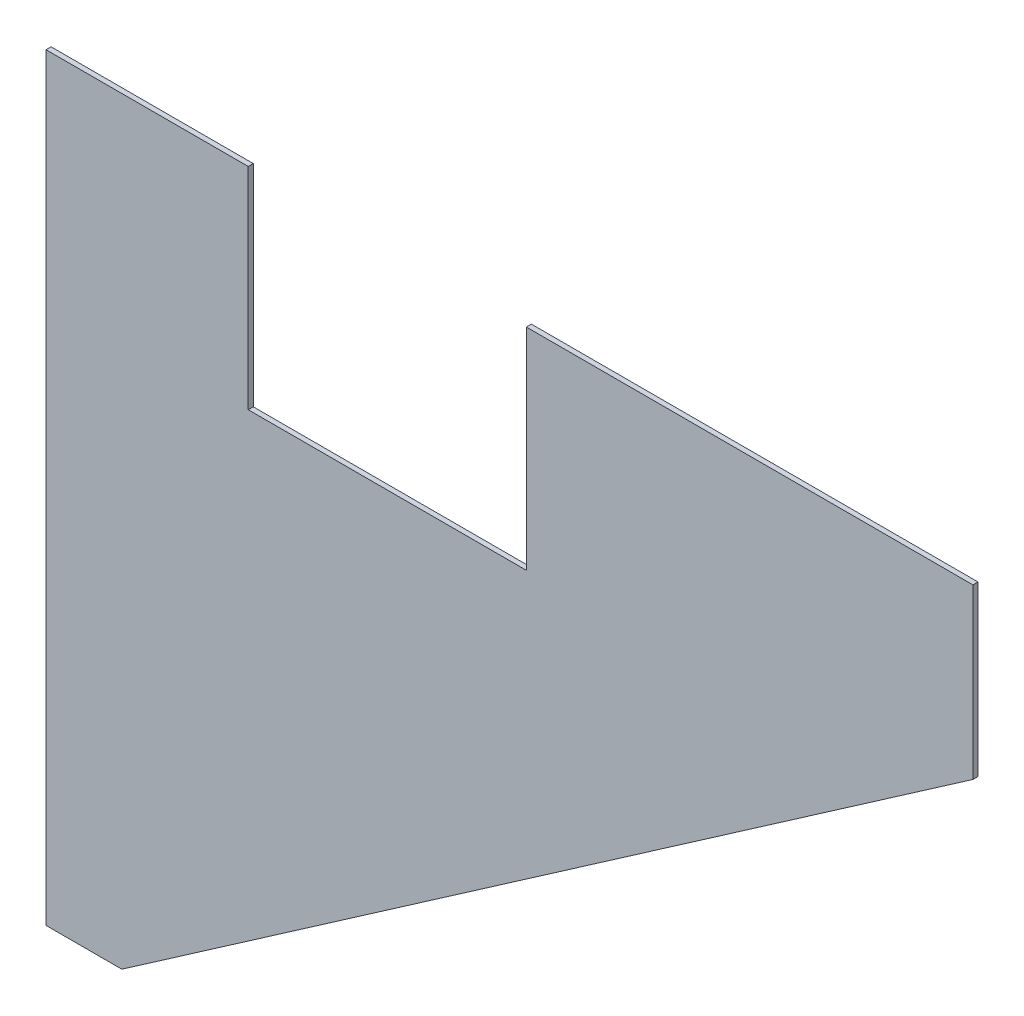
SolidWorks part; units mm, degrees
ref_plane "前视基准面" through (0, 0, 0) normal (0, 0, 1) x (1, 0, 0)
ref_plane "上视基准面" through (0, 0, 0) normal (0, 1, 0) x (1, 0, 0)
ref_plane "右视基准面" through (0, 0, 0) normal (1, 0, 0) x (0, 0, -1)
sketch "草图1" plane through (0, 0, 0) normal (0, 0, 1) x (1, 0, 0)
  line L0 (0, -100) -> (0, 800)
  line L1 (0, 800) -> (1100, 800)
  line L2 (1100, 800) -> (1100, 600)
  line L3 (0, -100) -> (90, -100)
  line L4 (1100, 600) -> (90, -100)
  dimension "D1" = 1100
  dimension "D2" = 900
  dimension "D3" = 200
  dimension "D4" = 90
extrude "凸台-拉伸1" add sketch "草图1" along normal blind 6
sketch "草图2" plane through (0, 0, 6) normal (0, 0, 1) x (1, 0, 0)
  line L0 (365, 800) -> (365, 559.6263) construction
  line L1 (0, 800) -> (0, -100) construction
  line L2 (1100, 800) -> (0, 800) construction
  line L3 (240, 800) -> (490, 800)
  line L4 (240, 800) -> (240, 550)
  line L5 (240, 550) -> (490, 550)
  line L6 (490, 800) -> (490, 550)
  dimension "D1" = 250
  dimension "D2" = 250
  dimension "D3" = 365
extrude "切除-拉伸1" cut sketch "草图2" against normal through all
sketch "草图3" plane through (0, 0, 6) normal (0, 0, 1) x (1, 0, 0)
  line L1 (490, 550) -> (570, 550)
  line L2 (490, 550) -> (490, 800)
  line L3 (490, 800) -> (570, 800)
  line L4 (570, 550) -> (570, 800)
  dimension "D1" = 80
extrude "切除-拉伸2" cut sketch "草图3" against normal blind 10
